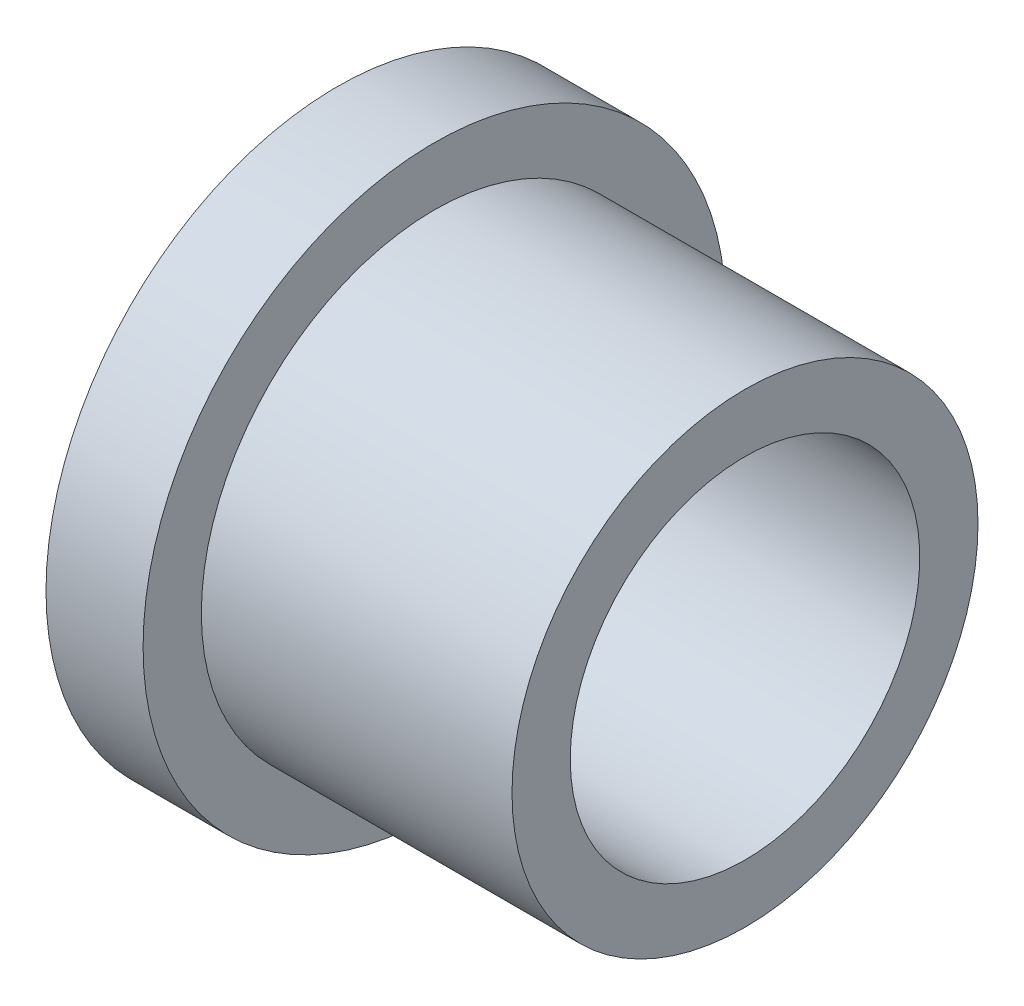
SolidWorks part; units mm, degrees
ref_plane "Front Plane" through (0, 0, 0) normal (0, 0, 1) x (1, 0, 0)
ref_plane "Top Plane" through (0, 0, 0) normal (0, 1, 0) x (1, 0, 0)
ref_plane "Right Plane" through (0, 0, 0) normal (1, 0, 0) x (0, 0, -1)
sketch "Sketch1" plane through (0, 0, 0) normal (0, 0, 1) x (1, 0, 0)
  line L0 (0, 0) -> (21228.064, 0) construction
  line L1 (0, 0) -> (0, -21228.064) construction
  line L2 (0, 0) -> (0, 15)
  line L3 (0, 15) -> (5, 15)
  line L4 (5, 15) -> (5, 12)
  line L5 (5, 12) -> (21, 12)
  line L6 (21, 12) -> (21, 0)
  line L7 (21, 9) -> (0, 9)
  dimension "D1" = 30
  dimension "D2" = 24
  dimension "D3" = 21
  dimension "D4" = 16
  dimension "D5" = 3
revolve "Revolve1" add sketch "Sketch1" angle 360 about L0
